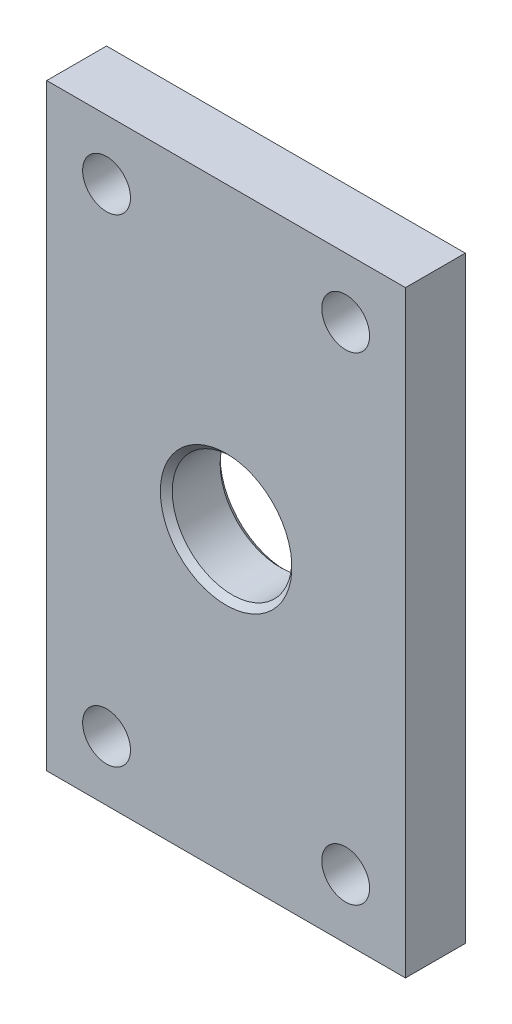
SolidWorks part; units mm, degrees
ref_plane "Front Plane" through (0, 0, 0) normal (1, 0, 0) x (0, 1, 0)
ref_plane "Top Plane" through (0, 0, 0) normal (0, 0, 1) x (0, 1, 0)
ref_plane "Right Plane" through (0, 0, 0) normal (0, 1, 0) x (-1, 0, 0)
sketch "Sketch1" plane through (0, 0, 0) normal (0, 0, 1) x (0, 1, 0)
  line L1 (-50, -30) -> (50, -30)
  line L2 (-50, -30) -> (-50, 30)
  line L3 (-50, 30) -> (50, 30)
  line L4 (50, -30) -> (50, 30)
  line L5 (-50, -30) -> (50, 30) construction
  line L6 (-50, 30) -> (50, -30) construction
  point P0 (0, 0)
extrude "Boss-Extrude1" add sketch "Sketch1" along normal mid plane 10
sketch "Sketch2" plane through (0, 0, 0) normal (0, 0, 1) x (0, 1, 0)
  circle A0 centre (-40, -20) radius 4
extrude "Cut-Extrude2" cut sketch "Sketch2" against normal up to next from offset 5
sketch "Sketch3" plane through (0, 0, 0) normal (0, 0, 1) x (0, 1, 0)
  circle A0 centre (40, -20) radius 4
  circle A1 centre (-40, 20) radius 4
  circle A2 centre (40, 20) radius 4
extrude "Cut-Extrude4" cut sketch "Sketch3" against normal up to next from offset 5
sketch "Sketch4" plane through (0, 0, 0) normal (0, 0, 1) x (0, 1, 0)
  circle A0 centre (0, 0) radius 10
extrude "Cut-Extrude6" cut sketch "Sketch4" against normal up to next from offset 5
chamfer "Chamfer1" distance 1 angle 45 2 edges at (-10, 0, -5) (10, 0, 5)
